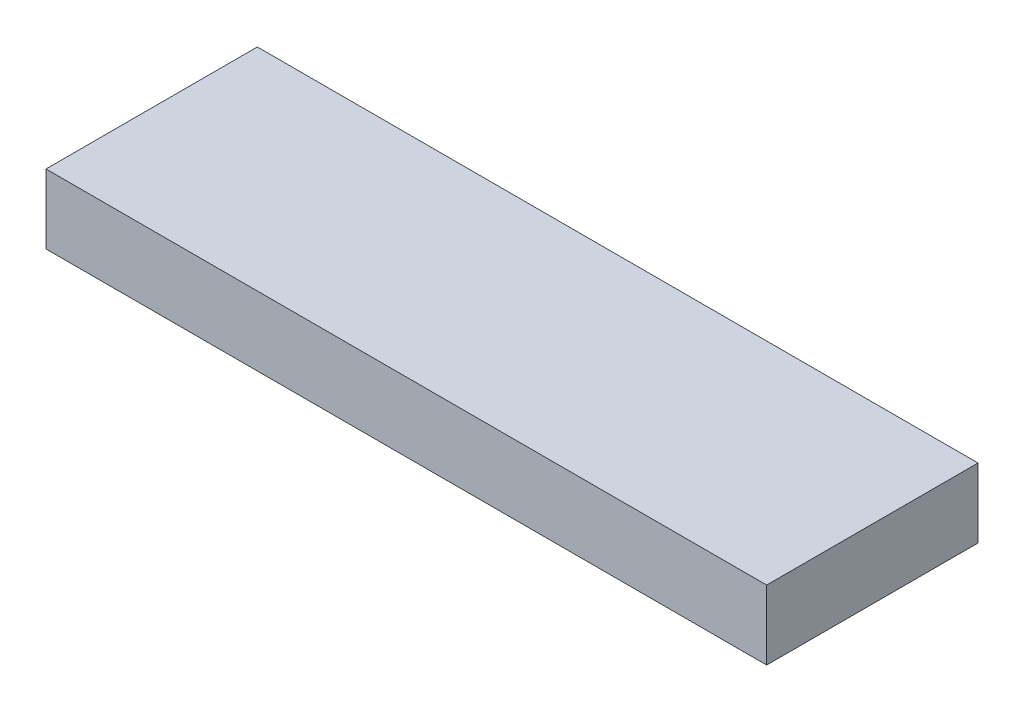
SolidWorks part; units mm, degrees
ref_plane "Front" through (0, 0, 0) normal (0, 0, 1) x (1, 0, 0)
ref_plane "Top" through (0, 0, 0) normal (0, 1, 0) x (1, 0, 0)
ref_plane "Right" through (0, 0, 0) normal (1, 0, 0) x (0, 0, -1)
sketch "ｽｹｯﾁ1" plane through (0, 0, 0) normal (0, 1, 0) x (1, 0, 0)
  line L1 (-104, 30.5) -> (104, 30.5)
  line L2 (-104, 30.5) -> (-104, -30.5)
  line L3 (-104, -30.5) -> (104, -30.5)
  line L4 (104, 30.5) -> (104, -30.5)
  line L5 (0, -30.5) -> (0, 30.5) construction
  line L6 (-104, 0) -> (104, 0) construction
  point P0 (0, 0)
  dimension "D1" = 208
  dimension "D2" = 61
extrude "ﾎﾞｽ - 押し出し1" add sketch "ｽｹｯﾁ1" along normal blind 20
